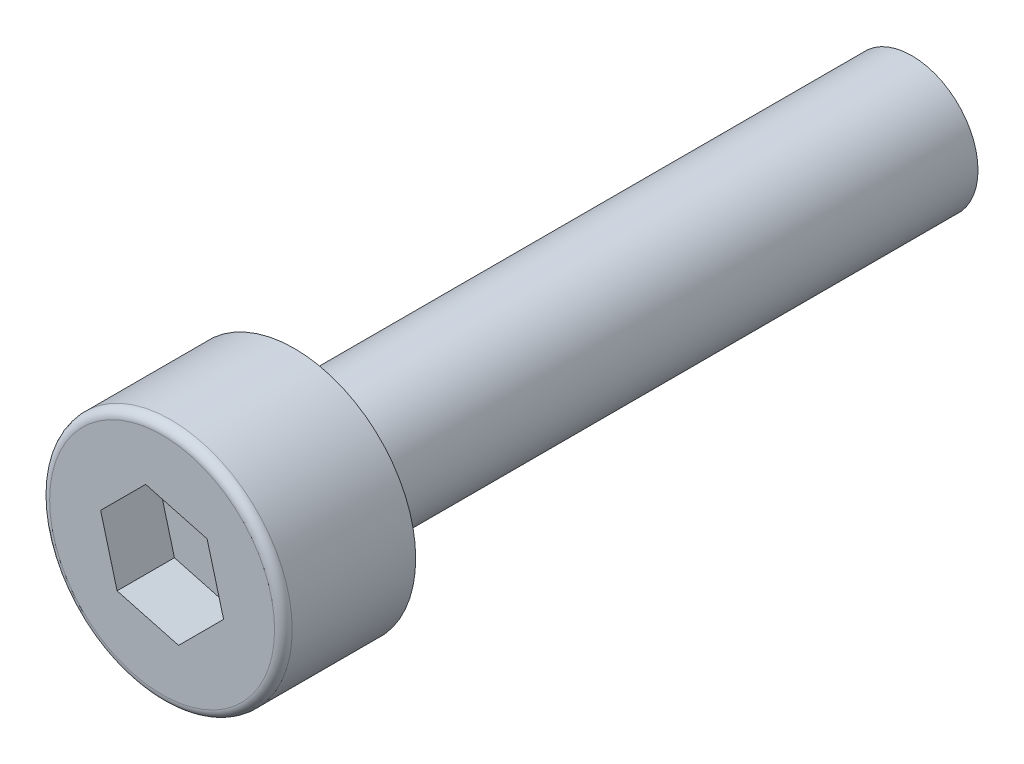
SolidWorks part; units mm, degrees
ref_plane "前视基准面" through (0, 0, 0) normal (0, 0, 1) x (1, 0, 0)
ref_plane "上视基准面" through (0, 0, 0) normal (0, 1, 0) x (1, 0, 0)
ref_plane "右视基准面" through (0, 0, 0) normal (1, 0, 0) x (0, 0, -1)
sketch "草图1" plane through (0, 0, 0) normal (0, 0, 1) x (1, 0, 0)
  circle A0 centre (0, 0) radius 2.75
  dimension "D1" = 5.5
extrude "凸台-拉伸1" add sketch "草图1" along normal blind 3
sketch "草图2" plane through (0, 0, 3) normal (0, 0, 1) x (1, 0, 0)
  line L1 (-1.0206, -1.0206) -> (0.3736, -1.3942)
  line L2 (0.3736, -1.3942) -> (1.3942, -0.3736)
  line L3 (1.3942, -0.3736) -> (1.0206, 1.0206)
  line L4 (1.0206, 1.0206) -> (-0.3736, 1.3942)
  line L5 (-0.3736, 1.3942) -> (-1.3942, 0.3736)
  line L6 (-1.3942, 0.3736) -> (-1.0206, -1.0206)
  circle A0 centre (0, 0) radius 1.25 construction
  dimension "D1" = 2.5
extrude "切除-拉伸1" cut sketch "草图2" against normal blind 1.3
sketch "草图3" plane through (0, 0, 0) normal (0, 0, -1) x (-1, 0, 0)
  circle A0 centre (0, 0) radius 1.5
  dimension "D1" = 3
extrude "凸台-拉伸2" add sketch "草图3" along normal blind 14
fillet "圆角1" radius 0.2 1 edges at (2.75, 0, 3)
